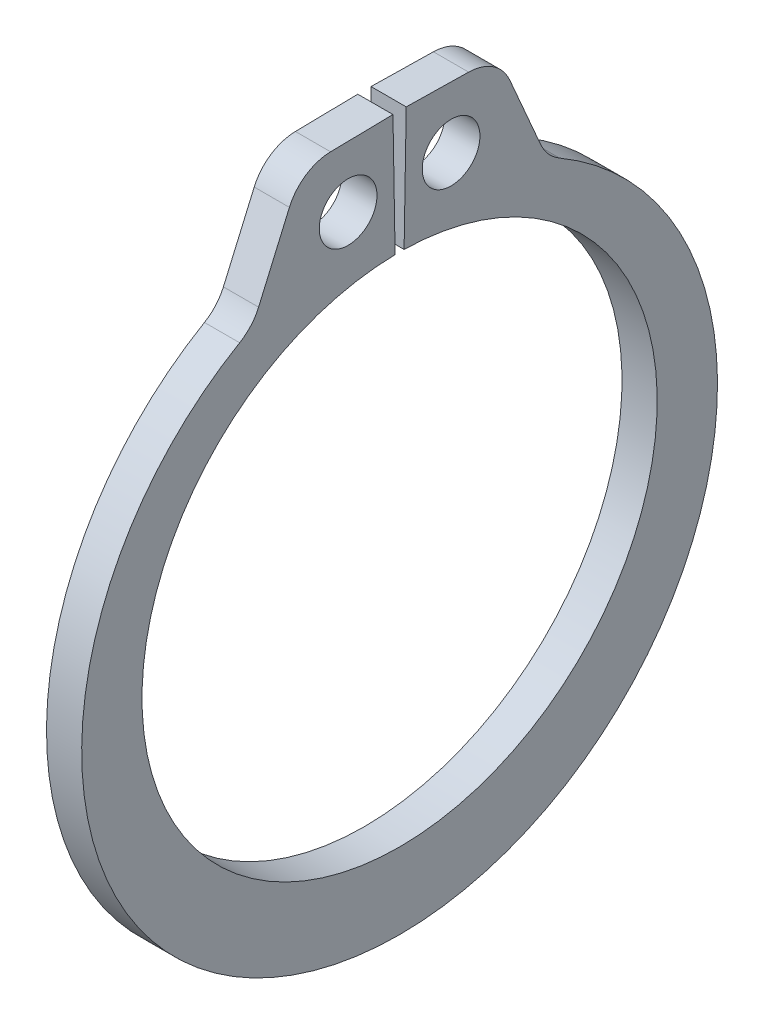
SolidWorks part; units mm, degrees
material "Cast Carbon Steel"
ref_plane "Front" through (0, 0, 0) normal (0, 0, 1) x (1, 0, 0)
ref_plane "Top" through (0, 0, 0) normal (0, 1, 0) x (1, 0, 0)
ref_plane "Right" through (0, 0, 0) normal (1, 0, 0) x (0, 0, -1)
sketch "Sketch1" plane through (0, 0, 0) normal (1, 0, 0) x (0, 0, -1)
  line L0 (0, 0) -> (0, 4.6482) construction
  line L1 (-0.0811, 4.6475) -> (-0.1197, 6.857)
  line L2 (0.1197, 6.857) -> (1.7768, 6.828)
  line L3 (1.7768, 6.828) -> (2.656, 4.8007)
  line L4 (0.0811, 4.6475) -> (0.1197, 6.857)
  line L5 (-0.1197, 6.857) -> (-1.7768, 6.828)
  line L6 (-1.7768, 6.828) -> (-2.656, 4.8007)
  line L7 (-2.656, 4.8007) -> (-2.2502, 4.0672) construction
  line L8 (2.656, 4.8007) -> (2.2502, 4.0672) construction
  line L9 (0, -4.6482) -> (0, -6.0198) construction
  line L10 (-1.7768, 6.828) -> (-0.0811, 4.6475) construction
  line L11 (0, 4.6482) -> (0, 6.858) construction
  line L12 (-4.6482, 0) -> (4.6482, 0) construction
  circle A0 centre (0, 0) radius 4.6482 construction
  arc A1 (-0.0811, 4.6475) -> (0.0811, 4.6475) centre (0, 0) ccw
  circle A3 centre (0, 0) radius 7.874 construction
  circle A4 centre (-0.929, 5.7378) radius 0.5207
  circle A5 centre (0.929, 5.7378) radius 0.5207
  arc A6 (-2.656, 4.8007) -> (2.656, 4.8007) centre (0, -0.2836) ccw
  point P0 (0, -6.0198)
  dimension "A" = 9.2964
  dimension "Hole" = 1.0414
  dimension "Smin" = 0.8382
  dimension "H" = 2.2098
  dimension "D2" = 1.6573
  dimension "Angle" = 1
extrude "Extrude1" add sketch "Sketch1" along normal mid plane 0.635
fillet "Fillet1" radius 0.8255 4 edges at (0, 4.8007, 2.656) (0, 4.8007, -2.656) (0, 6.828, 1.7768) (0, 6.828, -1.7768)
sketch "Sketch2" plane through (0, 0, 0) normal (0, 0, 1) x (1, 0, 0)
  line L0 (-3.5433, 0) -> (9.1567, 0)
  line L1 (9.1567, 0) -> (9.1567, -5.1562)
  line L2 (-0.3683, -5.1562) -> (-3.2385, -5.1562)
  line L3 (9.1567, -5.1562) -> (0.3683, -5.1562)
  line L4 (0.3683, -5.1562) -> (0.3683, -4.8514)
  line L5 (0.3683, -4.8514) -> (-0.3683, -4.8514)
  line L6 (-0.3683, -4.8514) -> (-0.3683, -5.1562)
  line L7 (-0.3683, -5.1562) -> (-3.5433, -5.1562) construction
  line L8 (-3.5433, -5.1562) -> (-3.5433, 0) construction
  line L9 (9.1567, 0) -> (76.391, 0) construction
  line L10 (-3.2385, -5.1562) -> (-3.5433, -4.8514)
  line L11 (-3.5433, -4.8514) -> (-3.5433, 0)
  point P10 (0, -4.8514)
  dimension "D2" = 12.7
  dimension "D3" = 3.175
  dimension "D1" = 45
revolve "Revolve1" [suppressed] add sketch "Sketch2" angle 360 about L9
delete or keep bodies "Body-Delete1" [suppressed] type delete bodies bodies 122
move or copy body "Body-Move/Copy1" [suppressed] bodies to move or copy 121
equation "\"D2@Sketch2\" = \"D1@Extrude1\"*20"
equation "\"D3@Sketch2\" = \"D2@Sketch2\"/4"
equation "\"D2@Sketch1\" = \"H@Sketch1\"*.75"
